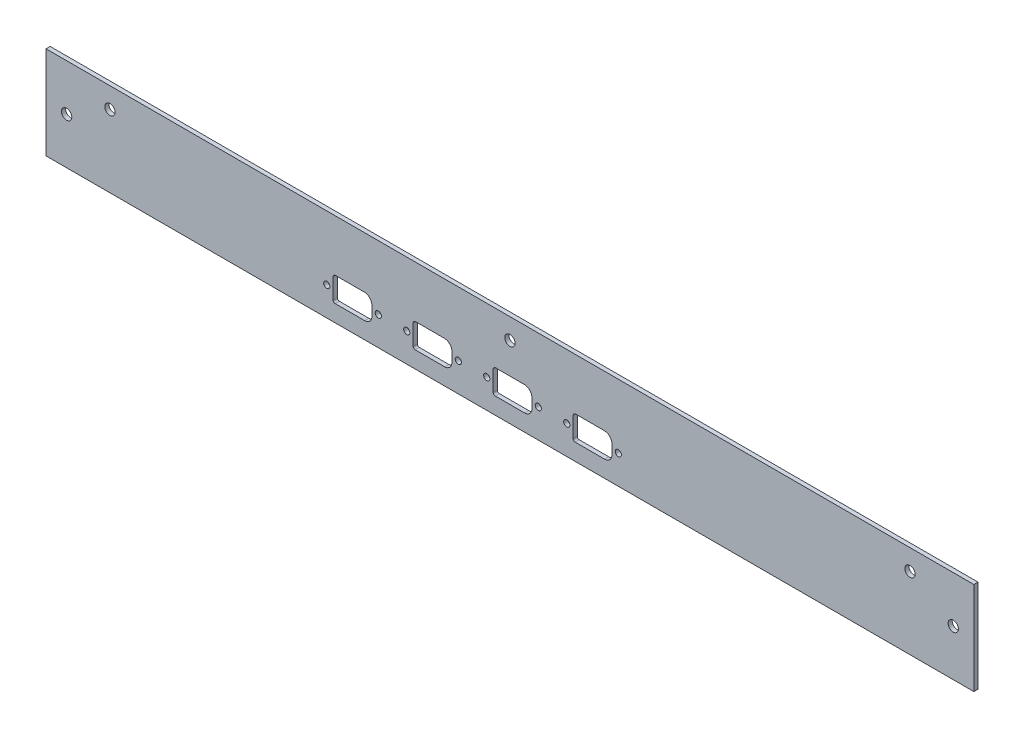
SolidWorks part; units mm, degrees
material "1345 Alloy"
ref_plane "Front Plane" through (0, 0, 0) normal (0, 0, 1) x (1, 0, 0)
ref_plane "Top Plane" through (0, 0, 0) normal (0, 1, 0) x (1, 0, 0)
ref_plane "Right Plane" through (0, 0, 0) normal (1, 0, 0) x (0, 0, -1)
sketch "Sketch1" plane through (0, 0, 0) normal (0, 0, 1) x (1, 0, 0)
  line L1 (-225, 22.5) -> (225, 22.5)
  line L2 (-225, 22.5) -> (-225, -22.5)
  line L3 (-225, -22.5) -> (225, -22.5)
  line L4 (225, 22.5) -> (225, -22.5)
  line L5 (-225, 22.5) -> (225, -22.5) construction
  line L6 (-225, -22.5) -> (225, 22.5) construction
  point P0 (0, 0)
  dimension "D1" = 450
  dimension "D2" = 45
extrude "Boss-Extrude1" add sketch "Sketch1" along normal blind 2
sketch "Sketch2" plane through (0, 0, 2) normal (0, 0, 1) x (1, 0, 0)
  line L0 (-28.1375, -8.55) -> (-25.0375, -8.55) construction
  line L1 (-31.6625, -14.4) -> (-45.9375, -14.4)
  line L2 (-45.7375, -2.5) -> (-31.8625, -2.5)
  line L3 (-46.9375, -13.4) -> (-46.9375, -3.7)
  line L4 (-28.1375, -10.875) -> (-28.1375, -6.225)
  line L5 (7.1375, -14.4) -> (-7.1375, -14.4)
  line L6 (-6.9375, -2.5) -> (6.9375, -2.5)
  line L7 (-8.1375, -13.4) -> (-8.1375, -3.7)
  line L8 (10.6625, -10.875) -> (10.6625, -6.225)
  line L9 (45.9375, -14.4) -> (31.6625, -14.4)
  line L10 (31.8625, -2.5) -> (45.7375, -2.5)
  line L11 (30.6625, -13.4) -> (30.6625, -3.7)
  line L12 (49.4625, -10.875) -> (49.4625, -6.225)
  line L17 (10.6625, -8.55) -> (13.7625, -8.55) construction
  line L18 (0, 22.5) -> (-225, 22.5) construction
  line L23 (-25.0375, -8.55) -> (-11.2375, -8.55) construction
  line L24 (-50.0375, -8.55) -> (-46.9375, -8.55) construction
  line L25 (-11.2375, -8.55) -> (-8.1375, -8.55) construction
  line L26 (27.5625, -8.55) -> (30.6625, -8.55) construction
  line L27 (-11.2375, -8.55) -> (-8.1375, -8.55) construction
  line L28 (13.7625, -8.55) -> (27.5625, -8.55) construction
  line L29 (49.4625, -8.55) -> (52.5625, -8.55) construction
  line L30 (-63.8375, -8.55) -> (-50.0375, -8.55) construction
  line L31 (-66.9375, -8.55) -> (-63.8375, -8.55) construction
  line L32 (0, -2.5) -> (0, 22.5) construction
  line L33 (-70.4625, -14.4) -> (-84.7375, -14.4)
  line L34 (-84.5375, -2.5) -> (-70.6625, -2.5)
  line L35 (-85.7375, -13.4) -> (-85.7375, -3.7)
  line L36 (-66.9375, -10.875) -> (-66.9375, -6.225)
  line L37 (-88.8375, -8.55) -> (-85.7375, -8.55) construction
  arc A0 (-28.1375, -10.875) -> (-31.6625, -14.4) centre (-31.6625, -10.875) cw
  arc A1 (-28.1375, -6.225) -> (-31.8625, -2.5) centre (-31.8625, -6.225) ccw
  arc A2 (-45.9375, -14.4) -> (-46.9375, -13.4) centre (-45.9375, -13.4) cw
  arc A3 (-46.9375, -3.7) -> (-45.7375, -2.5) centre (-45.7375, -3.7) cw
  arc A4 (10.6625, -10.875) -> (7.1375, -14.4) centre (7.1375, -10.875) cw
  arc A5 (10.6625, -6.225) -> (6.9375, -2.5) centre (6.9375, -6.225) ccw
  arc A6 (-7.1375, -14.4) -> (-8.1375, -13.4) centre (-7.1375, -13.4) cw
  arc A7 (-8.1375, -3.7) -> (-6.9375, -2.5) centre (-6.9375, -3.7) cw
  arc A8 (49.4625, -10.875) -> (45.9375, -14.4) centre (45.9375, -10.875) cw
  arc A9 (49.4625, -6.225) -> (45.7375, -2.5) centre (45.7375, -6.225) ccw
  arc A10 (31.6625, -14.4) -> (30.6625, -13.4) centre (31.6625, -13.4) cw
  arc A11 (30.6625, -3.7) -> (31.8625, -2.5) centre (31.8625, -3.7) cw
  circle A20 centre (-50.0375, -8.55) radius 1.5
  circle A21 centre (-25.0375, -8.55) radius 1.5
  circle A22 centre (-11.2375, -8.55) radius 1.5
  circle A23 centre (13.7625, -8.55) radius 1.5
  circle A24 centre (27.5625, -8.55) radius 1.5
  circle A25 centre (52.5625, -8.55) radius 1.5
  arc A26 (-66.9375, -10.875) -> (-70.4625, -14.4) centre (-70.4625, -10.875) cw
  arc A27 (-66.9375, -6.225) -> (-70.6625, -2.5) centre (-70.6625, -6.225) ccw
  arc A28 (-84.7375, -14.4) -> (-85.7375, -13.4) centre (-84.7375, -13.4) cw
  arc A29 (-85.7375, -3.7) -> (-84.5375, -2.5) centre (-84.5375, -3.7) cw
  circle A30 centre (-88.8375, -8.55) radius 1.5
  circle A31 centre (-63.8375, -8.55) radius 1.5
  dimension "D5" = 3
  dimension "D6" = 3
  dimension "D1" = 3
  dimension "D2" = 3
  dimension "D3" = 3
  dimension "D4" = 3
  dimension "D20" = 3
  dimension "D21" = 3
  dimension "D7" = 25
  dimension "D8" = 25
  dimension "D9" = 13.8
  dimension "D10" = 13.8
  dimension "D11" = 25
  dimension "D12" = 25
  dimension "D13" = 5.85
  dimension "D14" = 5.85
  dimension "D15" = 5.85
  dimension "D16" = 5.85
  dimension "D17" = 5.85
  dimension "D18" = 5.85
  dimension "D19" = 13.8
  dimension "D22" = 5.85
  dimension "D23" = 5.85
extrude "Cut-Extrude1" cut sketch "Sketch2" against normal through all
sketch "Sketch3" plane through (0, 0, 2) normal (0, 0, 1) x (1, 0, 0)
  line L0 (-225, 22.5) -> (-215, 22.5) construction
  line L1 (225, 22.5) -> (-225, 22.5) construction
  line L2 (-215, 22.5) -> (-215, 0) construction
  line L3 (225, -22.5) -> (225, 22.5) construction
  line L4 (-194, 12.4954) -> (194, 12.4954) construction
  line L5 (-225, 22.5) -> (-225, -22.5) construction
  line L7 (0, 22.5) -> (0, 12.5) construction
  circle A0 centre (-215, 0) radius 2.5
  circle A1 centre (215, 0) radius 2.5
  circle A2 centre (-194, 12.4954) radius 2.5
  circle A3 centre (194, 12.4954) radius 2.5
  circle A4 centre (0, 12.5) radius 2.5
  dimension "D3" = 5
  dimension "D6" = 5
  dimension "D7" = 5
  dimension "D8" = 5
  dimension "D9" = 5
  dimension "D1" = 10
  dimension "D2" = 22.5
  dimension "D4" = 2
  dimension "D5" = 10
  dimension "D10" = 10
  dimension "D11" = 31
  dimension "D12" = 31
extrude "Cut-Extrude2" cut sketch "Sketch3" against normal through all
